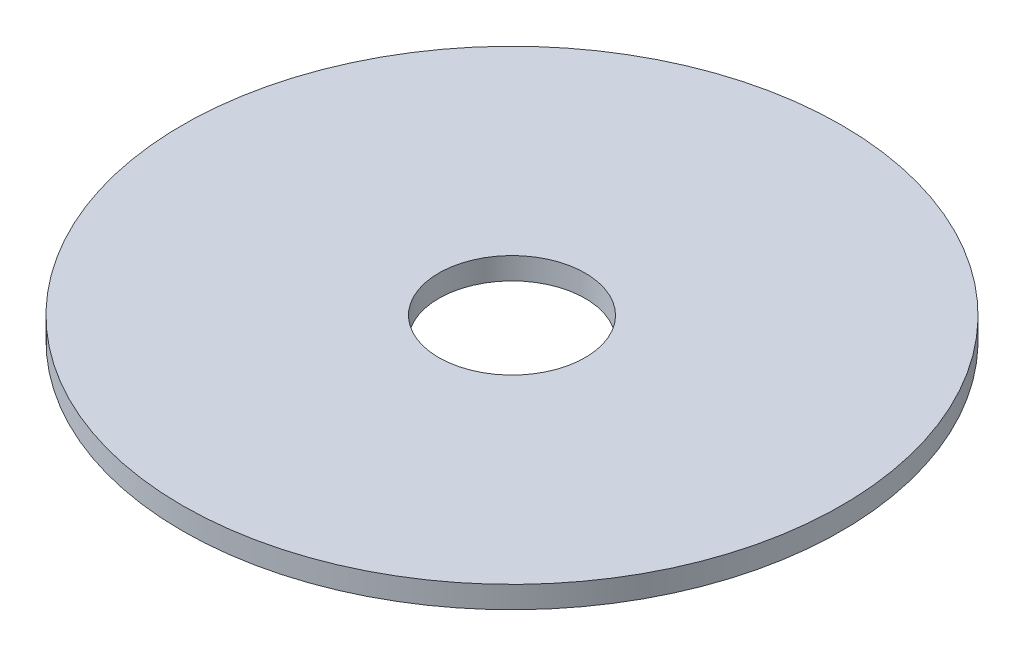
SolidWorks part; units mm, degrees
ref_plane "Front Plane" through (0, 0, 0) normal (0, 0, 1) x (1, 0, 0)
ref_plane "Top Plane" through (0, 0, 0) normal (0, 1, 0) x (1, 0, 0)
ref_plane "Right Plane" through (0, 0, 0) normal (1, 0, 0) x (0, 0, -1)
sketch "Sketch1" plane through (0, 0, 0) normal (0, 1, 0) x (1, 0, 0)
  circle A0 centre (0, 0) radius 45
  circle A1 centre (0, 0) radius 10
  dimension "D1" = 90
  dimension "D2" = 20
extrude "Boss-Extrude1" add sketch "Sketch1" along normal mid plane 3
